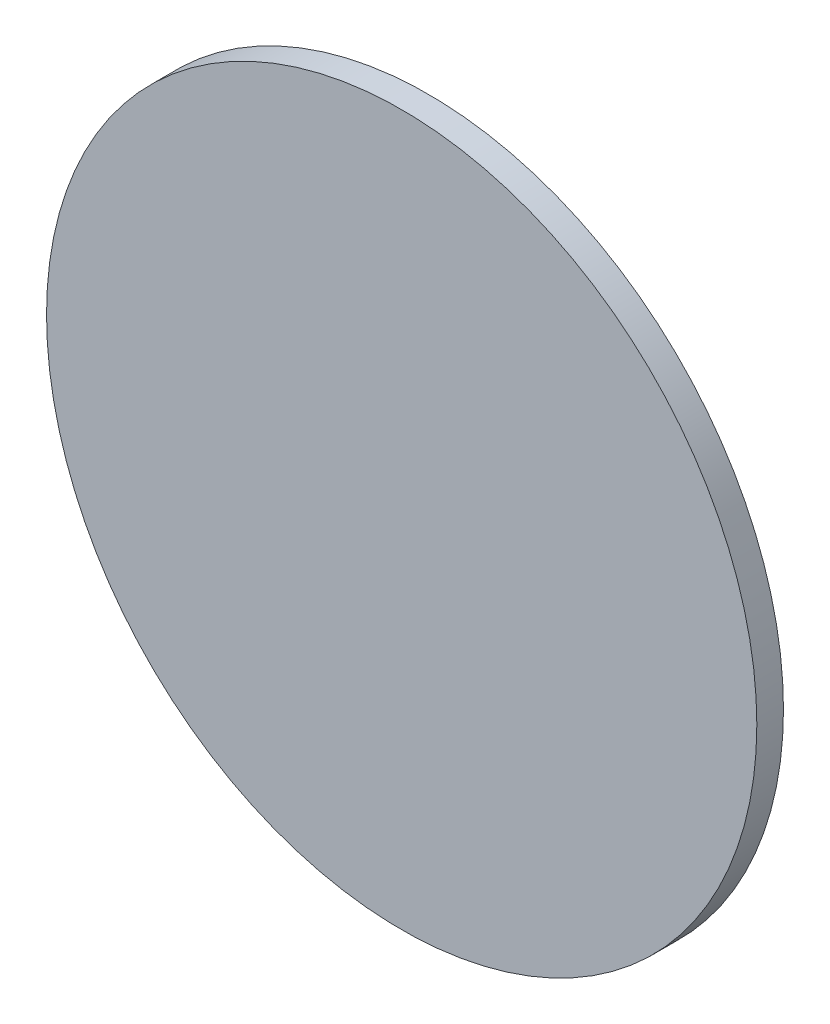
SolidWorks part; units mm, degrees
material "Silicon"
ref_plane "Front Plane" through (0, 0, 0) normal (0, 0, 1) x (1, 0, 0)
ref_plane "Top Plane" through (0, 0, 0) normal (0, 1, 0) x (1, 0, 0)
ref_plane "Right Plane" through (0, 0, 0) normal (1, 0, 0) x (0, 0, -1)
sketch "Sketch1" plane through (0, 0, 0) normal (0, 0, 1) x (1, 0, 0)
  circle A0 centre (0, 0) radius 4
  dimension "D1" = 8
extrude "Boss-Extrude1" add sketch "Sketch1" against normal blind 0.3
